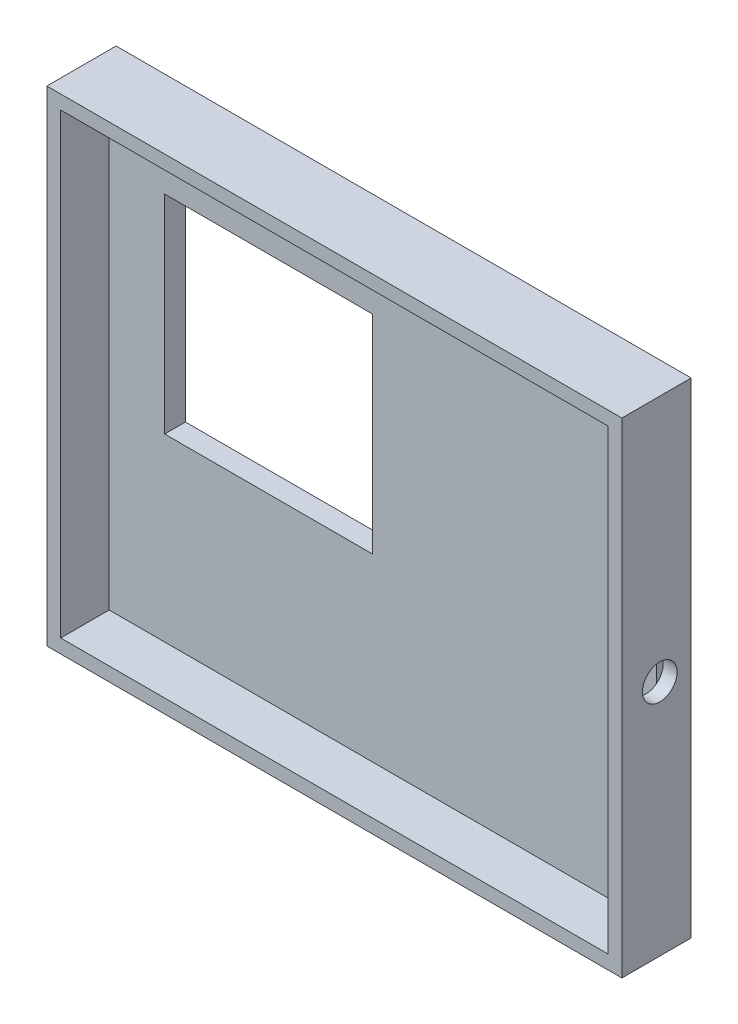
SolidWorks part; units mm, degrees
ref_plane "Front Plane" through (0, 0, 0) normal (0, 0, 1) x (1, 0, 0)
ref_plane "Top Plane" through (0, 0, 0) normal (0, 1, 0) x (1, 0, 0)
ref_plane "Right Plane" through (0, 0, 0) normal (1, 0, 0) x (0, 0, -1)
sketch "Sketch1" plane through (0, 0, 0) normal (0, 0, 1) x (1, 0, 0)
  line L1 (0, 0) -> (83, 0)
  line L2 (0, 0) -> (0, 70)
  line L3 (0, 70) -> (83, 70)
  line L4 (83, 0) -> (83, 70)
  dimension "D1" = 83
  dimension "D2" = 70
extrude "Boss-Extrude1" add sketch "Sketch1" along normal blind 10
sketch "Sketch3" plane through (0, 0, 10) normal (0, 0, 1) x (1, 0, 0)
  line L0 (0, 0) -> (83, 0) construction
  line L1 (2, 2) -> (81, 2)
  line L2 (2, 2) -> (2, 68)
  line L3 (2, 68) -> (81, 68)
  line L4 (81, 2) -> (81, 68)
  line L5 (0, 70) -> (0, 0) construction
  dimension "D1" = 66
  dimension "D2" = 79
  dimension "D3" = 2
  dimension "D4" = 2
extrude "Cut-Extrude1" cut sketch "Sketch3" against normal blind 7
sketch "Sketch4" plane through (0, 0, 0) normal (0, 0, -1) x (-1, 0, 0)
  line L0 (-83, 70) -> (0, 70) construction
  line L1 (-40, 58) -> (-10, 58)
  line L2 (-40, 58) -> (-40, 28)
  line L3 (-40, 28) -> (-10, 28)
  line L4 (-10, 58) -> (-10, 28)
  line L5 (0, 70) -> (0, 0) construction
  dimension "D1" = 12
  dimension "D2" = 10
  dimension "D3" = 30
  dimension "D4" = 30
extrude "Cut-Extrude2" cut sketch "Sketch4" against normal blind 7
sketch "Sketch5" plane through (83, 0, 0) normal (1, 0, 0) x (0, 0, -1)
  circle A0 centre (-4.5321, 34.2801) radius 2.5
  dimension "D1" = 5
extrude "Cut-Extrude3" cut sketch "Sketch5" against normal blind 2
